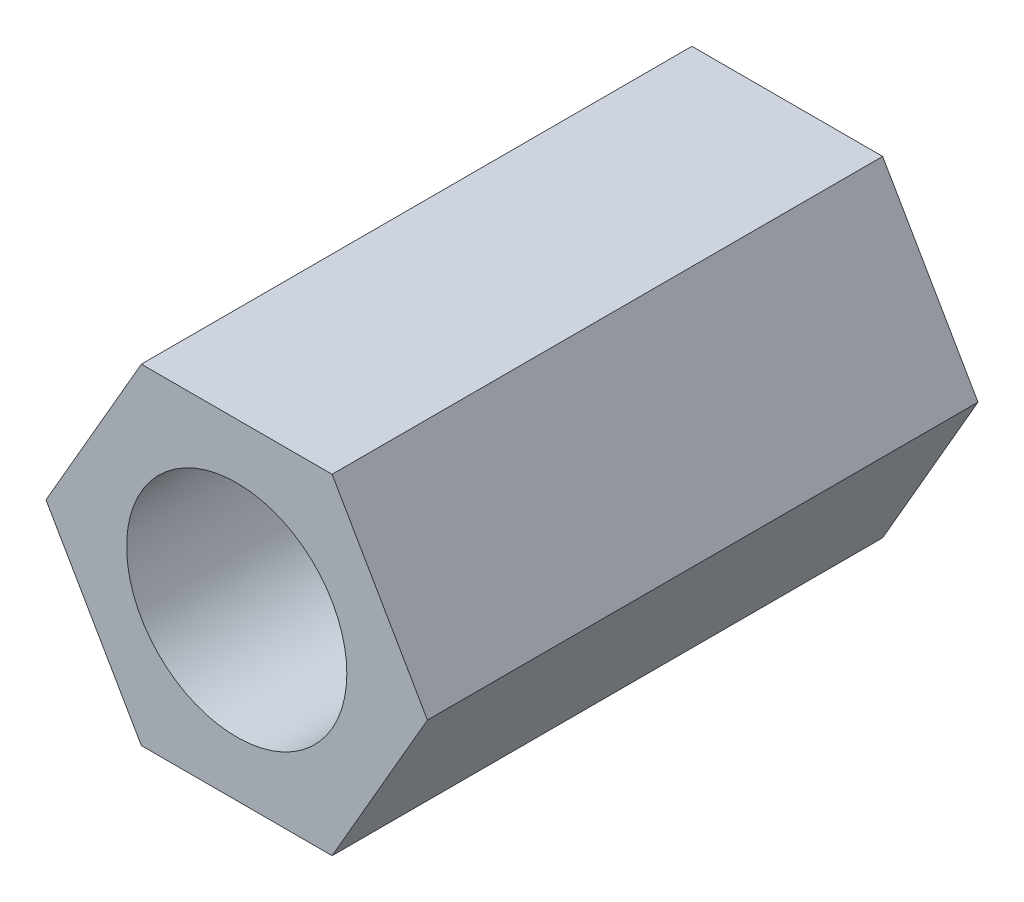
SolidWorks part; units mm, degrees
ref_plane "前视基准面" through (0, 0, 0) normal (0, 0, 1) x (1, 0, 0)
ref_plane "上视基准面" through (0, 0, 0) normal (0, 1, 0) x (1, 0, 0)
ref_plane "右视基准面" through (0, 0, 0) normal (1, 0, 0) x (0, 0, -1)
sketch "草图1" plane through (0, 0, 0) normal (0, 0, 1) x (1, 0, 0)
  line L1 (1.7321, 0) -> (0.866, 1.5)
  line L2 (0.866, 1.5) -> (-0.866, 1.5)
  line L3 (-0.866, 1.5) -> (-1.7321, 0)
  line L4 (-1.7321, 0) -> (-0.866, -1.5)
  line L5 (-0.866, -1.5) -> (0.866, -1.5)
  line L6 (0.866, -1.5) -> (1.7321, 0)
  circle A0 centre (0, 0) radius 1
  circle A1 centre (0, 0) radius 1.5 construction
  dimension "D1" = 2
  dimension "D2" = 3
extrude "凸台-拉伸1" add sketch "草图1" along normal blind 5
